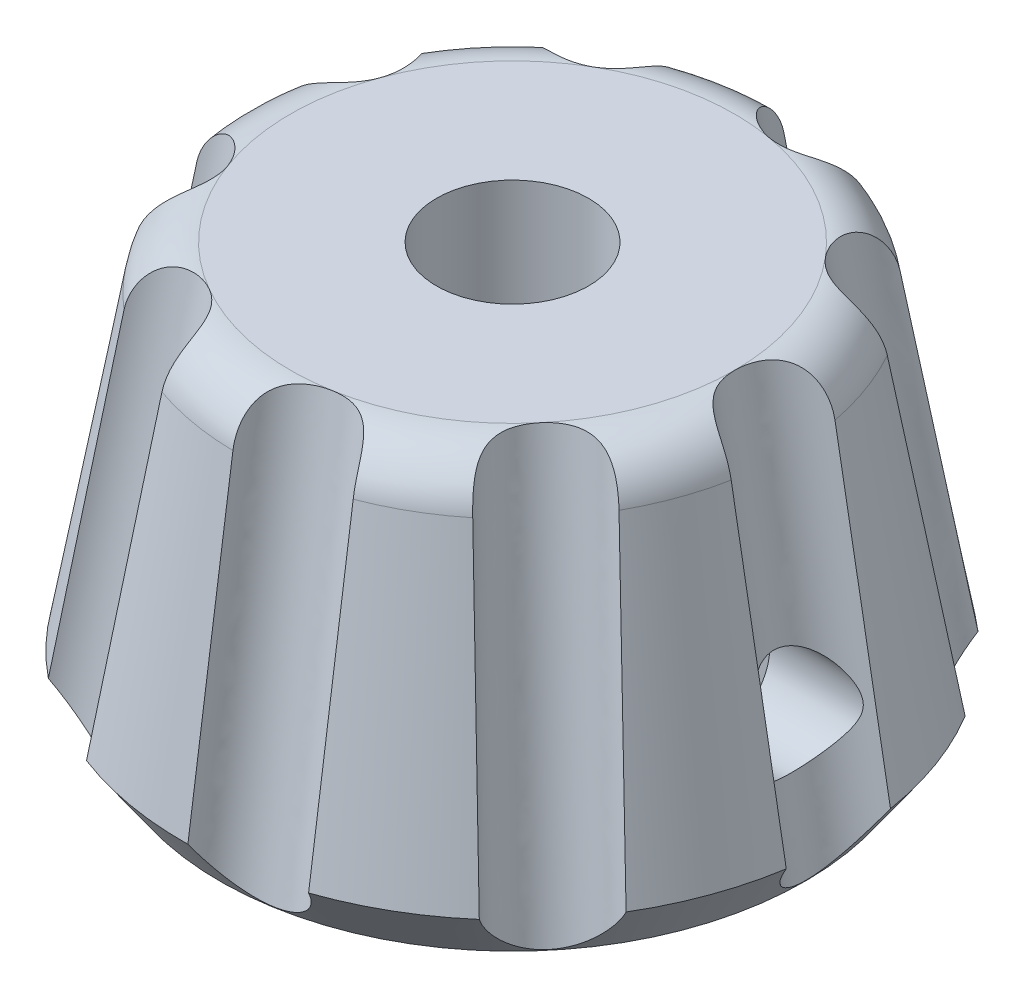
SolidWorks part; units mm, degrees
ref_plane "Front Plane" through (0, 0, 0) normal (0, 0, 1) x (1, 0, 0)
ref_plane "Top Plane" through (0, 0, 0) normal (0, 1, 0) x (1, 0, 0)
ref_plane "Right Plane" through (0, 0, 0) normal (1, 0, 0) x (0, 0, -1)
sketch "Sketch1" plane through (0, 0, 0) normal (0, 0, 1) x (1, 0, 0)
  line L0 (2.8, 0) -> (2.8, 15)
  line L1 (2.8, 15) -> (9.8551, 15)
  line L2 (9.8551, 15) -> (12.5, 0)
  line L3 (12.5, 0) -> (2.8, 0)
  line L4 (0, 0) -> (0, 15) construction
  dimension "D1" = 5.6
  dimension "D2" = 15
  dimension "D3" = 25
  dimension "D4" = 80
revolve "Revolve1" add sketch "Sketch1" angle 360 about L4
fillet "Fillet1" radius 2 1 edges at (0, 15, -9.8551)
chamfer "Chamfer1" distance 2 angle 45 1 edges at (0, 0, -12.5)
sketch "Sketch2" plane through (0, 15, 0) normal (0, 1, 0) x (1, 0, 0)
  line L0 (12.5, 0) -> (2.8, 0) construction
  circle A0 centre (10.1465, 0) radius 1.9696
  circle A3 centre (0, 0) radius 10.1465 construction
  circle A4 centre (0, 0) radius 8.1769 construction
extrude "Cut-Extrude1" cut sketch "Sketch2" along direction (0.1736, -0.9848, 0) on the side against the normal through all
pattern_circular "CirPattern1" count 9 over 360 about axis through (0, 15, 0) along (0, 1, 0) of "Cut-Extrude1"
ref_plane "Plane1" through (4.675, 0, 0) normal (1, 0, 0) x (0, 0, -1)
sketch "Sketch4" plane through (4.675, 0, 0) normal (1, 0, 0) x (0, 0, -1)
  line L0 (0, 0) -> (0, 15) construction
  line L1 (2.9, 3.3257) -> (2.9, 6.6743)
  line L2 (2.9, 6.6743) -> (0, 8.3486)
  line L3 (0, 8.3486) -> (-2.9, 6.6743)
  line L4 (-2.9, 6.6743) -> (-2.9, 3.3257)
  line L5 (-2.9, 3.3257) -> (0, 1.6514) construction
  line L6 (0, 1.6514) -> (2.9, 3.3257) construction
  line L7 (-2.9, 3.3257) -> (-2.9, 0)
  line L8 (-2.9, 0) -> (2.9, 0)
  line L9 (-10.7736, 0) -> (10.7736, 0) construction
  line L10 (2.9, 0) -> (2.9, 3.3257)
  circle A0 centre (0, 5) radius 2.9 construction
  dimension "D1" = 5.8
  dimension "D2" = 5
extrude "Cut-Extrude2" cut sketch "Sketch4" along normal blind 3
sketch "Sketch6" plane through (0, 0, 0) normal (1, 0, 0) x (0, 0, -1)
  circle A0 centre (0, 5) radius 1.8
  dimension "D1" = 3.6
extrude "Cut-Extrude3" cut sketch "Sketch6" along normal through all
